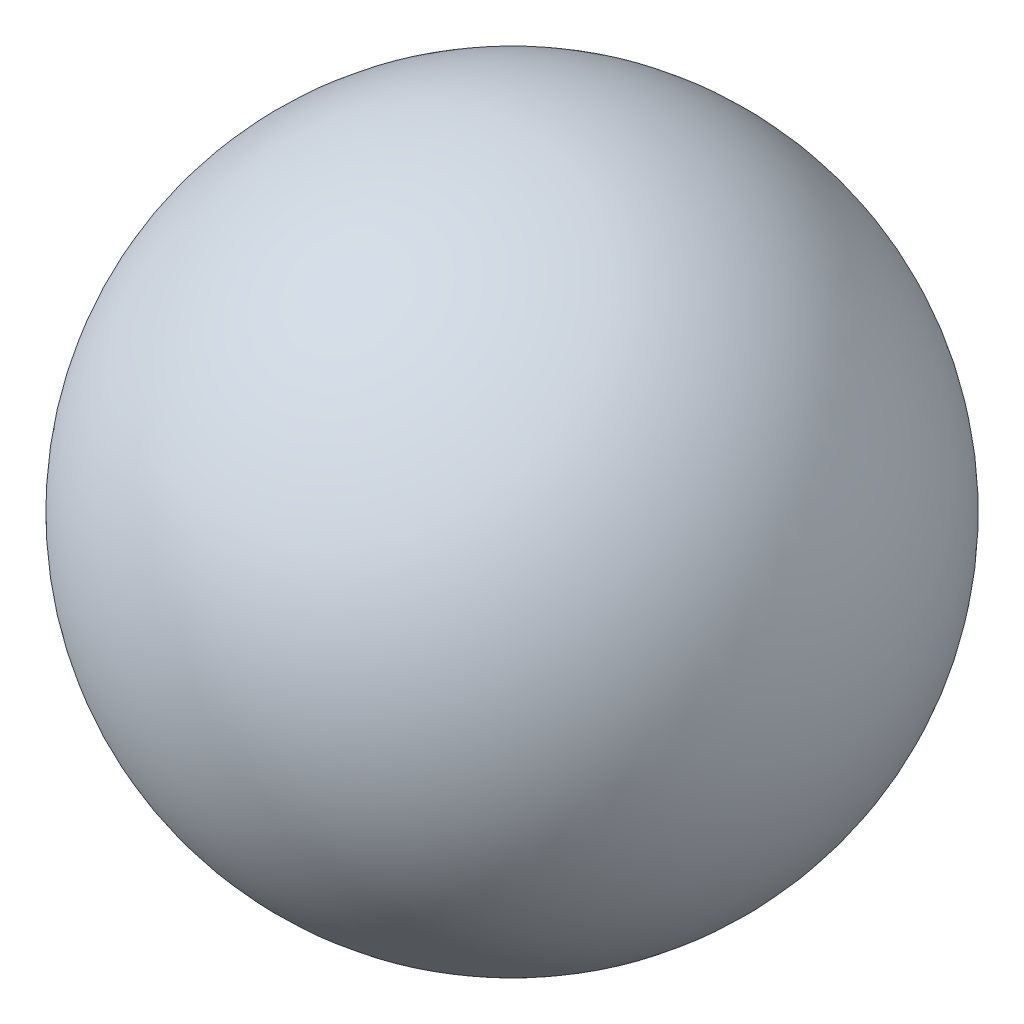
SolidWorks part; units mm, degrees
ref_plane "Front Plane" through (0, 0, 0) normal (0, 0, 1) x (1, 0, 0)
ref_plane "Top Plane" through (0, 0, 0) normal (0, 1, 0) x (1, 0, 0)
ref_plane "Right Plane" through (0, 0, 0) normal (1, 0, 0) x (0, 0, -1)
sketch "Sketch1" plane through (0, 0, 0) normal (0, 0, 1) x (1, 0, 0)
  line L0 (0, 53.3148) -> (0, -52.6327) construction
  line L1 (0, 20.32) -> (0, -20.32)
  arc A0 (0, 20.32) -> (0, -20.32) centre (0, 0) ccw
  dimension "D1" = 20.32
revolve "Revolve1" add sketch "Sketch1" angle 360 about L0
ref_plane "Plane1 - TANGENT PLANE" through (0, -20.32, 0) normal (0, 1, 0) x (1, 0, 0)
equation "\"D1@Sketch1\"=1.6/2"
